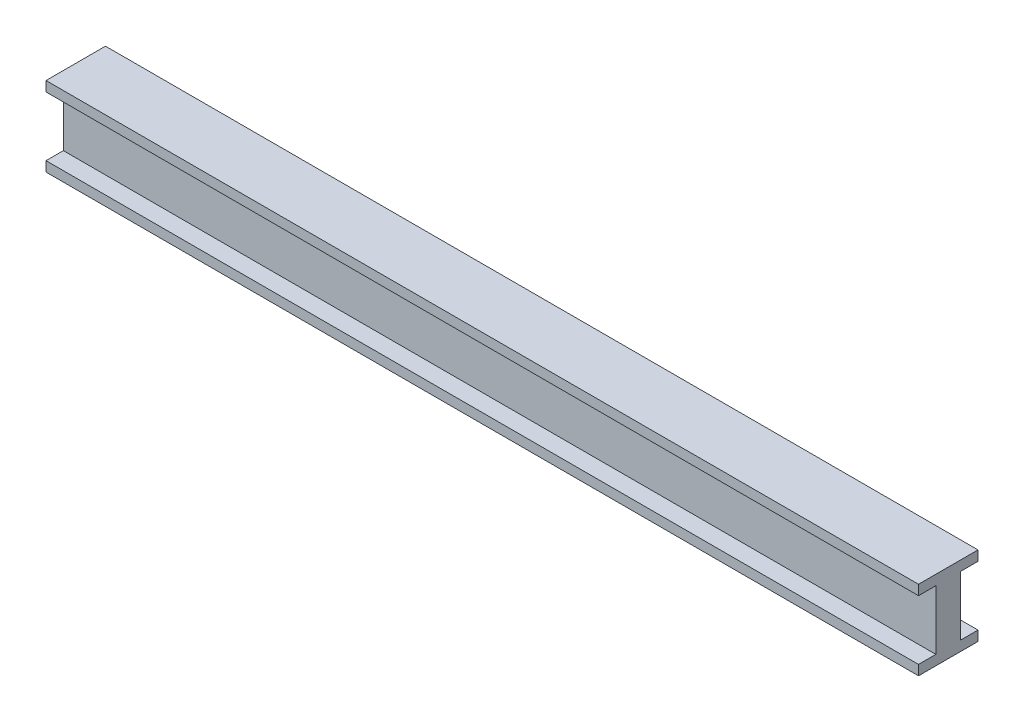
SolidWorks part; units mm, degrees
ref_plane "Front Plane" through (0, 0, 0) normal (0, 0, 1) x (1, 0, 0)
ref_plane "Top Plane" through (0, 0, 0) normal (0, 1, 0) x (1, 0, 0)
ref_plane "Right Plane" through (0, 0, 0) normal (1, 0, 0) x (0, 0, -1)
sketch "Sketch2" plane through (0, 0, 0) normal (1, 0, 0) x (0, 0, -1)
  line L1 (-19.05, 25.4) -> (19.05, 25.4)
  line L3 (-19.05, -25.4) -> (19.05, -25.4)
  line L5 (-19.05, 25.4) -> (19.05, -25.4) construction
  line L6 (-19.05, -25.4) -> (19.05, 25.4) construction
  line L7 (-19.05, 25.4) -> (19.05, 25.4)
  line L8 (-19.05, 25.4) -> (-19.05, 19.05)
  line L9 (-19.05, 19.05) -> (19.05, 19.05)
  line L10 (19.05, 25.4) -> (19.05, 19.05)
  line L11 (-19.05, -25.4) -> (19.05, -25.4)
  line L12 (-19.05, -25.4) -> (-19.05, -19.05)
  line L13 (-19.05, -19.05) -> (19.05, -19.05)
  line L14 (19.05, -25.4) -> (19.05, -19.05)
  line L15 (-7.9375, -19.05) -> (7.9375, -19.05)
  line L16 (-7.9375, -19.05) -> (-7.9375, 19.05)
  line L17 (-7.9375, 19.05) -> (7.9375, 19.05)
  line L18 (7.9375, -19.05) -> (7.9375, 19.05)
  line L19 (-7.9375, -19.05) -> (7.9375, 19.05) construction
  line L20 (-7.9375, 19.05) -> (7.9375, -19.05) construction
  point P0 (0, 0)
  point P12 (0, 0)
  dimension "D1" = 50.8
  dimension "D2" = 38.1
extrude "Boss-Extrude1" add sketch "Sketch2" along normal blind 558.8 contours L10 L1 L8 L9 | L13 L18 L9 L16 | L3 L14 L13 L12
